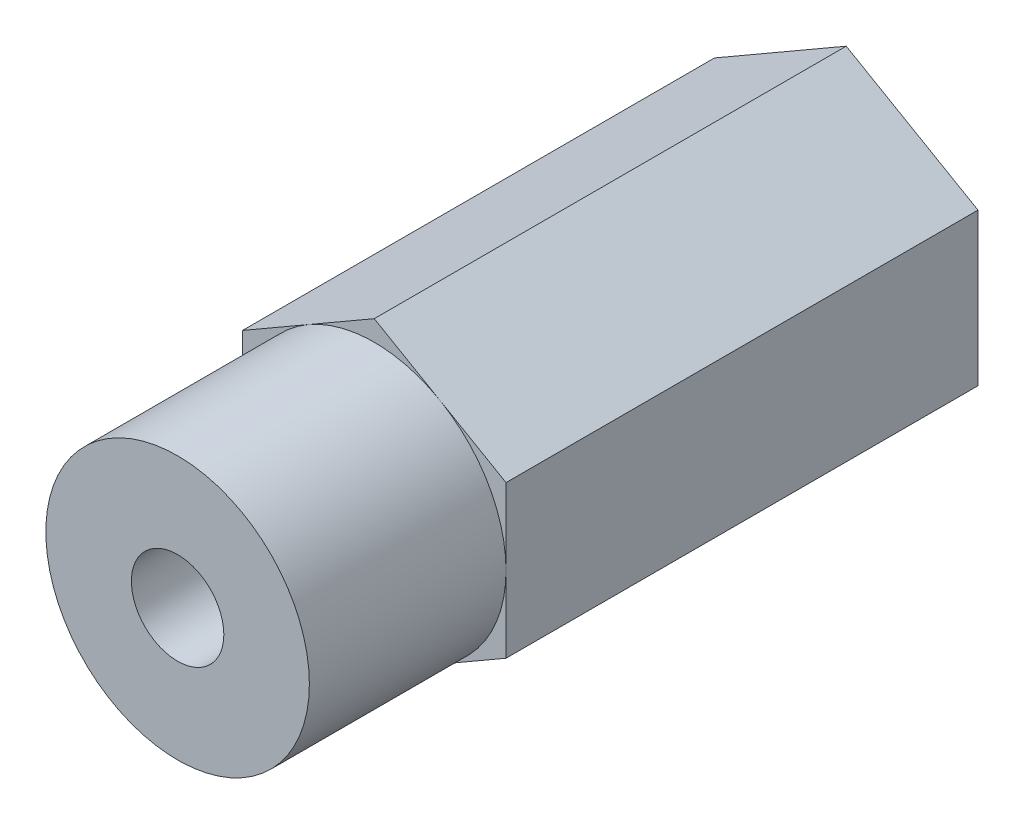
SolidWorks part; units mm, degrees
other "Markup1"
sketch "Sketch3" plane through (-2.2657, 2.2139, 10.2) normal (-0.1261, 0.9667, 0.2227) x (0.9256, 0.0339, 0.3769)
ref_plane "Front Plane" through (0, 0, 0) normal (0, 0, 1) x (1, 0, 0)
ref_plane "Top Plane" through (0, 0, 0) normal (0, 1, 0) x (1, 0, 0)
ref_plane "Right Plane" through (0, 0, 0) normal (1, 0, 0) x (0, 0, -1)
sketch "Sketch1" plane through (0, 0, 0) normal (0, 0, 1) x (1, 0, 0)
  line L1 (0, -2.3209) -> (2.01, -1.1605)
  line L2 (2.01, -1.1605) -> (2.01, 1.1605)
  line L3 (2.01, 1.1605) -> (0, 2.3209)
  line L4 (0, 2.3209) -> (-2.01, 1.1605)
  line L5 (-2.01, 1.1605) -> (-2.01, -1.1605)
  line L6 (-2.01, -1.1605) -> (0, -2.3209)
  circle A0 centre (0, 0) radius 2.01 construction
  dimension "D1" = 4.02
  dimension "D2" = 4.02
extrude "Boss-Extrude1" add sketch "Sketch1" along normal blind 10.2
sketch "Sketch2" plane through (0, 0, 10.2) normal (0, 0, 1) x (1, 0, 0)
  circle A2 centre (0, 0) radius 2.3209
  circle A3 centre (0, 0) radius 2.01
extrude "Cut-Extrude2" cut sketch "Sketch2" against normal blind 3
sketch "Sketch4" plane through (0, 0, 10.2) normal (0, 0, 1) x (1, 0, 0)
  circle A0 centre (0, 0) radius 0.705
  dimension "D1" = 1.41
extrude "Cut-Extrude3" cut sketch "Sketch4" against normal blind 7
